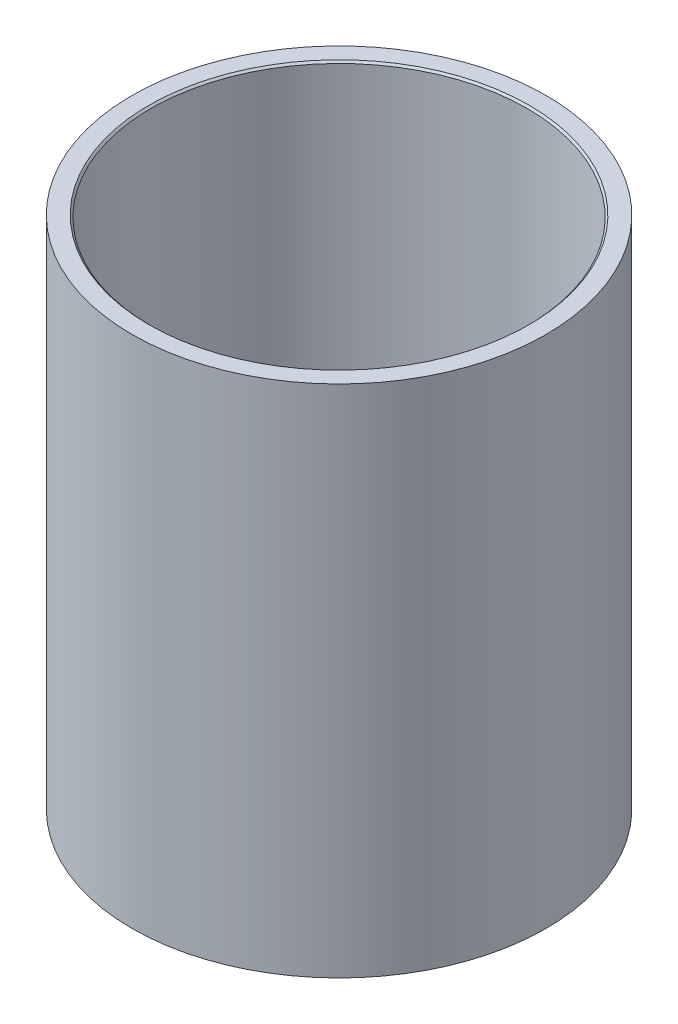
SolidWorks part; units mm, degrees
material "6063-T6"
ref_plane "Piano frontale" through (0, 0, 0) normal (0, 0, 1) x (1, 0, 0)
ref_plane "Piano superiore" through (0, 0, 0) normal (0, 1, 0) x (1, 0, 0)
ref_plane "Piano destro" through (0, 0, 0) normal (1, 0, 0) x (0, 0, -1)
sketch "Schizzo1" plane through (0, 0, 0) normal (0, 1, 0) x (1, 0, 0)
  circle A0 centre (0, 0) radius 30
  circle A1 centre (0, 0) radius 33
  dimension "D1" = 60
  dimension "D2" = 66
extrude "Estrusione-Estrusione1" add sketch "Schizzo1" along normal blind 82
chamfer "Smusso1" distance 0.3 angle 45 2 edges at (0, 0, 30) (0, 82, 30)
